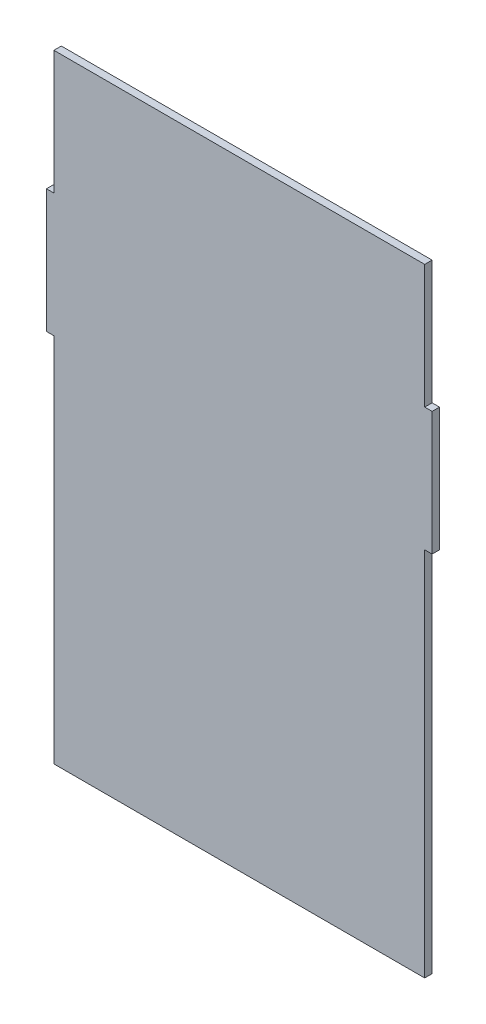
SolidWorks part; units mm, degrees
ref_plane "Alzado" through (0, 0, 0) normal (0, 0, 1) x (1, 0, 0)
ref_plane "Planta" through (0, 0, 0) normal (0, 1, 0) x (1, 0, 0)
ref_plane "Vista lateral" through (0, 0, 0) normal (1, 0, 0) x (0, 0, -1)
sketch "Croquis1" plane through (0, 0, 0) normal (0, 0, 1) x (1, 0, 0)
  line L0 (0, 200) -> (0, 250)
  line L1 (0, 0) -> (150, 0)
  line L2 (0, 0) -> (0, 150)
  line L3 (0, 250) -> (150, 250)
  line L4 (150, 0) -> (150, 150)
  line L5 (0, 200) -> (-3, 200)
  line L7 (0, 150) -> (-3, 150)
  line L8 (-3, 200) -> (-3, 150)
  line L9 (150, 150) -> (153, 150)
  line L11 (150, 200) -> (153, 200)
  line L12 (153, 150) -> (153, 200)
  line L13 (150, 200) -> (150, 250)
  dimension "D1" = 150
  dimension "D2" = 250
  dimension "D3" = 50
  dimension "D4" = 50
  dimension "D5" = 150
  dimension "D6" = 150
  dimension "D7" = 3
  dimension "D8" = 3
extrude "Saliente-Extruir1" add sketch "Croquis1" along normal blind 3
